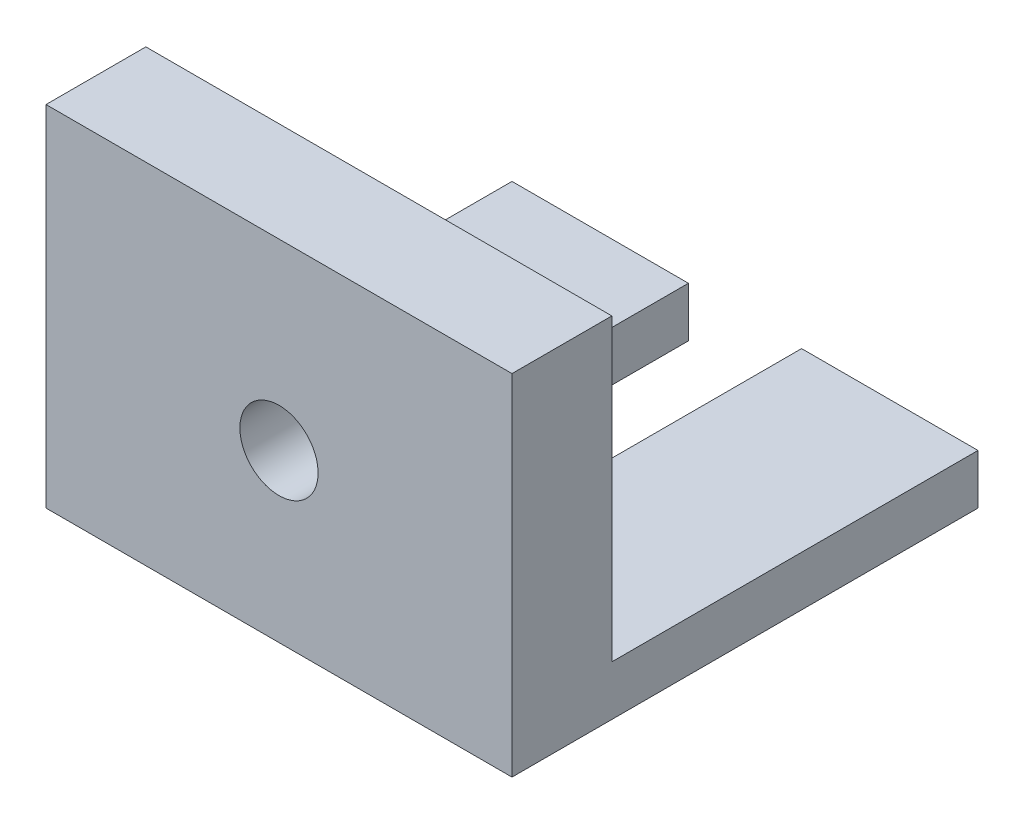
SolidWorks part; units mm, degrees
ref_plane "Front Plane" through (0, 0, 0) normal (0, 0, 1) x (1, 0, 0)
ref_plane "Top Plane" through (0, 0, 0) normal (0, 1, 0) x (1, 0, 0)
ref_plane "Right Plane" through (0, 0, 0) normal (1, 0, 0) x (0, 0, -1)
sketch "Sketch1" plane through (0, 0, 0) normal (0, 1, 0) x (1, 0, 0)
  line L1 (0, 0) -> (28, 0)
  line L2 (0, 0) -> (0, -28)
  line L3 (0, -28) -> (28, -28)
  line L4 (28, 0) -> (28, -28)
  dimension "D1" = 28
  dimension "D2" = 28
extrude "Boss-Extrude1" add sketch "Sketch1" along normal blind 25
sketch "Sketch2" plane through (0, 25, 0) normal (0, 1, 0) x (1, 0, 0)
  line L0 (28, -28) -> (28, 0) construction
  line L1 (0, 0) -> (28, 0)
  line L2 (0, 0) -> (0, -22)
  line L3 (0, -22) -> (28, -22)
  line L4 (28, 0) -> (28, -22)
  dimension "D1" = 22
extrude "Cut-Extrude1" cut sketch "Sketch2" against normal blind 22
sketch "Sketch3" plane through (0, 3, 0) normal (0, 1, 0) x (1, 0, 0)
  line L0 (28, 0) -> (0, 0) construction
  line L1 (10.6, 0) -> (17.4, 0)
  line L2 (10.6, 0) -> (10.6, -22)
  line L3 (10.6, -22) -> (17.4, -22)
  line L4 (17.4, 0) -> (17.4, -22)
  line L5 (0, -22) -> (28, -22) construction
  line L6 (0, 0) -> (0, -22) construction
  line L7 (28, -22) -> (28, 0) construction
  dimension "D1" = 6.8
  dimension "D2" = 22
  dimension "D3" = 10.6
  dimension "D4" = 10.6
extrude "Cut-Extrude2" cut sketch "Sketch3" against normal through all
sketch "Sketch4" plane through (0, 0, 22) normal (0, 0, -1) x (-1, 0, 0)
  line L0 (-10.6, 0) -> (-17.4, 0) construction
  line L1 (-28, 3) -> (-28, 25) construction
  line L2 (0, 3) -> (0, 25) construction
  circle A0 centre (-14, 10) radius 2.35
  dimension "D1" = 4.7
  dimension "D2" = 10
  dimension "D3" = 14
  dimension "D4" = 14
extrude "Cut-Extrude3" cut sketch "Sketch4" against normal through all
sketch "Sketch5" plane through (0, 25, 0) normal (0, 1, 0) x (1, 0, 0)
  line L1 (0, -28) -> (28, -28)
  line L2 (0, -28) -> (0, -22)
  line L3 (0, -22) -> (28, -22)
  line L4 (28, -28) -> (28, -22)
extrude "Cut-Extrude4" cut sketch "Sketch5" against normal blind 4
